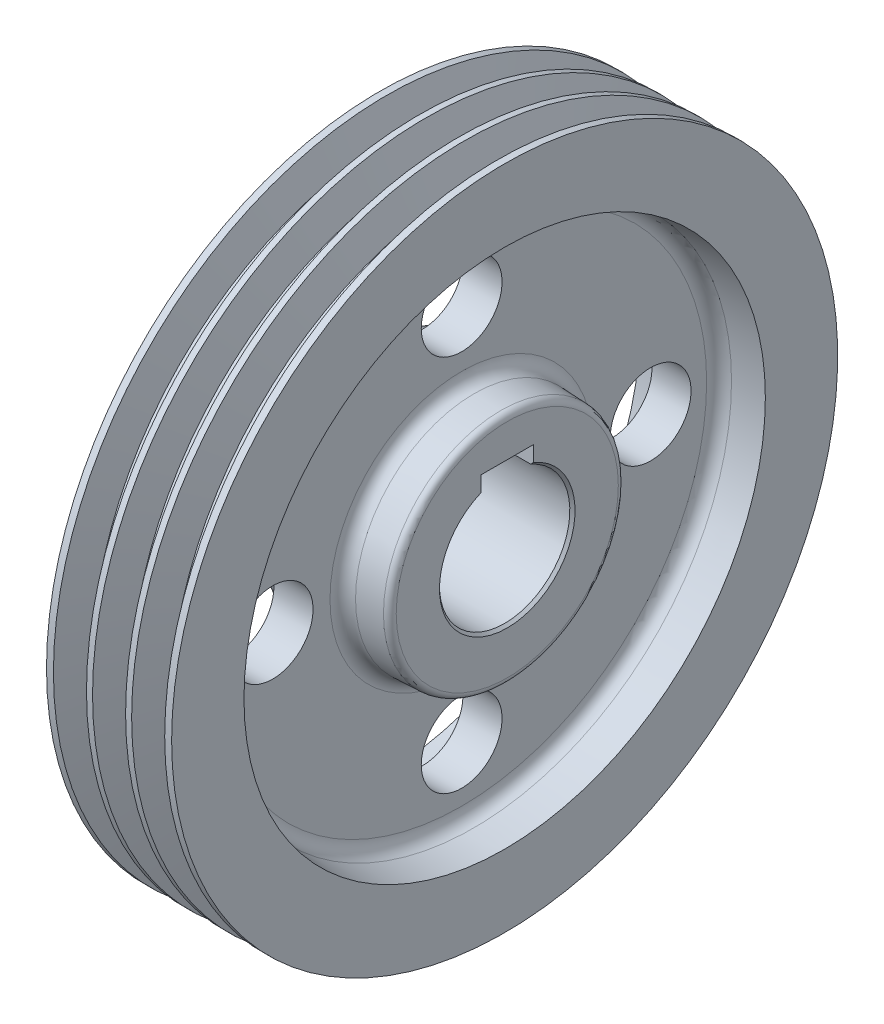
SolidWorks part; units mm, degrees
ref_plane "前视基准面" through (0, 0, 0) normal (0, 0, 1) x (1, 0, 0)
ref_plane "上视基准面" through (0, 0, 0) normal (0, 1, 0) x (1, 0, 0)
ref_plane "右视基准面" through (0, 0, 0) normal (1, 0, 0) x (0, 0, -1)
sketch "草图1" plane through (0, 0, 0) normal (0, 0, 1) x (1, 0, 0)
  line L0 (0, 0) -> (64.8368, 0) construction
  line L1 (-1, 25) -> (-1, 45)
  line L2 (0, 127.75) -> (48, 127.75)
  line L3 (48, 127.75) -> (48, 100)
  line L4 (-1, 45) -> (-30, 45) construction
  line L5 (16.5, 46.5311) -> (16.5, 99.3402)
  line L6 (49, 25) -> (-1, 25)
  line L7 (2.6592, 127.75) -> (6.1599, 116.3) construction
  line L8 (6.1599, 116.3) -> (11.8401, 116.3) construction
  line L9 (11.8401, 116.3) -> (15.3408, 127.75) construction
  line L10 (0, 125) -> (48, 125) construction
  line L11 (9, 116.3) -> (9, 25) construction
  line L12 (44, 100) -> (0, 100) construction
  line L13 (48, 100) -> (79, 100) construction
  line L14 (31.5, 98.5564) -> (31.5, 45.6998)
  line L15 (5, 45) -> (49, 45) construction
  line L16 (24, 25) -> (24, 127.75) construction
  line L17 (49, 45) -> (49, 25)
  line L18 (0, 100) -> (0, 127.75)
  line L19 (16.5, 88) -> (31.5, 88) construction
  line L20 (16.5, 57) -> (31.5, 57) construction
  line L21 (48, 100) -> (48, 88) construction
  line L22 (48, 88) -> (31.5, 88) construction
  line L23 (31.5, 57) -> (49, 57) construction
  line L24 (49, 57) -> (49, 45) construction
  line L25 (31.5, 98.5564) -> (48, 100)
  line L26 (16.5, 99.3402) -> (0, 100)
  line L27 (16.5, 46.5311) -> (-1, 45)
  line L28 (31.5, 45.6998) -> (49, 45)
  point P17 (3.5, 125)
  point P18 (14.5, 125)
  dimension "d2" = 200
  dimension "L" = 50
  dimension "B" = 48
  dimension "d" = 50
  dimension "d1" = 90
  dimension "D3" = 5
  dimension "D4" = 2.29
  dimension "dd" = 250
  dimension "f" = 9
  dimension "槽轮角" = 34
  dimension "bd" = 11
  dimension "hf" = 8.7
  dimension "ha" = 2.75
  dimension "da" = 255.5
  dimension "S" = 15
  dimension "S2" = 12
revolve "旋转1" add sketch "草图1" angle 360 about L0
sketch "草图2" plane through (0, 0, 0) normal (0, 0, 1) x (1, 0, 0)
  line L0 (11.8401, 116.3) -> (15.3408, 127.75) construction
  line L1 (6.1599, 116.3) -> (11.8401, 116.3) construction
  line L2 (2.6592, 127.75) -> (6.1599, 116.3) construction
  line L3 (11.8401, 116.3) -> (15.3408, 127.75)
  line L4 (6.1599, 116.3) -> (11.8401, 116.3)
  line L5 (2.6592, 127.75) -> (6.1599, 116.3)
  line L6 (2.6592, 127.75) -> (15.3408, 127.75)
  line L7 (0, 0) -> (123, 0) construction
revolve "切除-旋转1" cut sketch "草图2" angle 360 about L7
pattern_linear "轮槽数" count 3 spacing 15 along (1, 0, 0) of "切除-旋转1"
chamfer "倒角1" distance 1 2 edges at (-1, 0, 25) (49, 0, 25)
sketch "草图4" plane through (-1, 0, 0) normal (-1, 0, 0) x (0, 0, 1)
  line L1 (-10, 22.9129) -> (10, 22.9129)
  line L2 (-10, 22.9129) -> (-10, 29.9)
  line L3 (-10, 29.9) -> (10, 29.9)
  line L4 (10, 22.9129) -> (10, 29.9)
  circle A0 centre (0, 0) radius 25 construction
  point P6 (5.1, 29.9)
  dimension "键槽高度" = 29.9
  dimension "键槽宽度" = 20
  dimension "t1" = 4.9
extrude "切除-拉伸1" cut sketch "草图4" against normal through all
fillet "圆角1" radius 5 4 edges at (31.5, 0, 98.5564) (16.5, 0, 46.5311) (16.5, 0, 99.3402) (31.5, 0, 45.6998)
fillet "圆角2" radius 2.5 2 edges at (49, 0, 45) (-1, 0, 45)
sketch "草图5" plane through (0, 0, 0) normal (1, 0, 0) x (0, 0, -1)
  line L0 (0, 116.3) -> (0, 25) construction
  circle A0 centre (0, 72.5) radius 15.5
extrude "切除-拉伸2" cut sketch "草图5" along normal through all
pattern_circular "圆孔个数" count 4 over 360 about axis through (0, 0, 0) along (1, 0, 0) of "切除-拉伸2"
equation "\"B@草图1\" =  ( \"z@轮槽数\" - 1 )  * \"e@轮槽数\" +2 *  \"f@草图1\""
equation "\"键槽高度@草图4\" = \"d@草图1\" / 2 + \"t1@草图4\""
